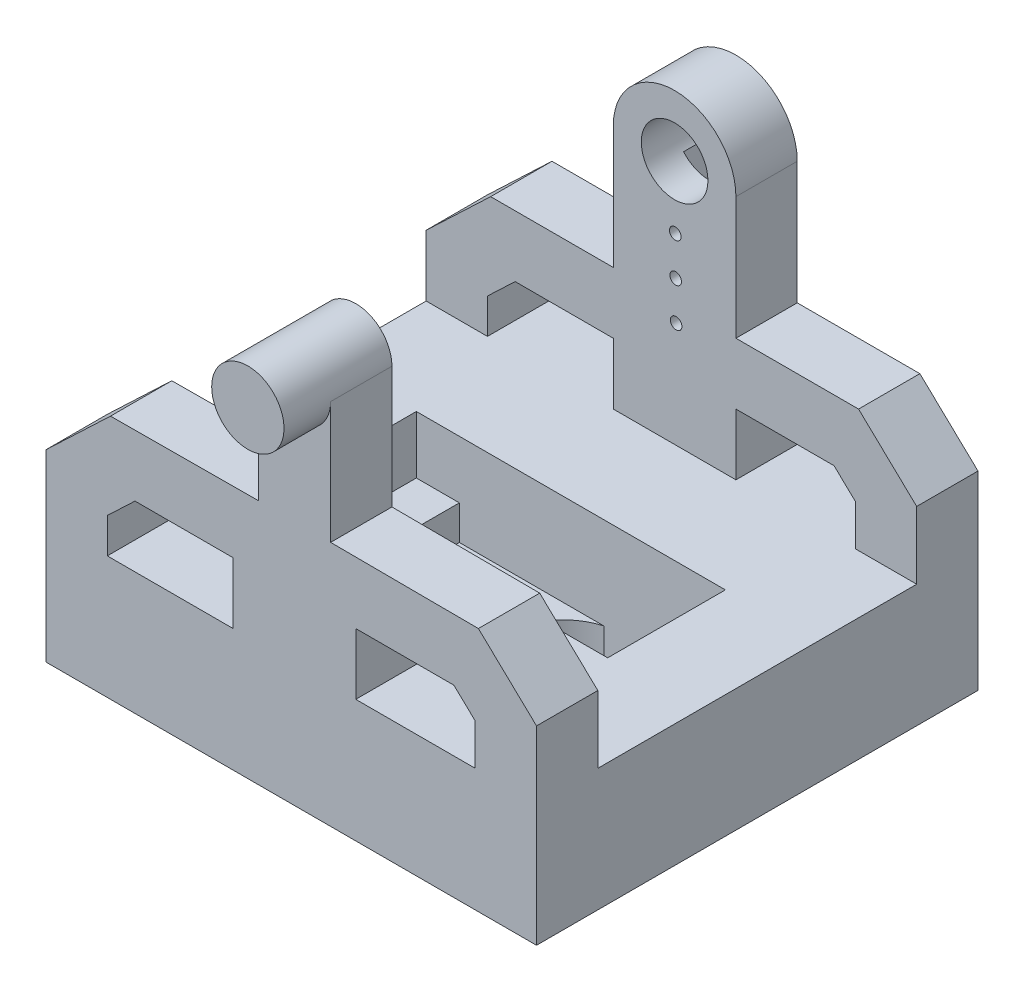
SolidWorks part; units mm, degrees
material "ABS PC"
ref_plane "Front Plane" through (0, 0, 0) normal (0, 0, 1) x (1, 0, 0)
ref_plane "Top Plane" through (0, 0, 0) normal (0, 1, 0) x (1, 0, 0)
ref_plane "Right Plane" through (0, 0, 0) normal (1, 0, 0) x (0, 0, -1)
sketch "Sketch1" plane through (0, 0, 0) normal (0, 1, 0) x (1, 0, 0)
  line L1 (-25.4, -22.86) -> (25.4, -22.86)
  line L2 (-25.4, -22.86) -> (-25.4, 22.86)
  line L3 (-25.4, 22.86) -> (25.4, 22.86)
  line L4 (25.4, -22.86) -> (25.4, 22.86)
  line L5 (-25.4, -22.86) -> (25.4, 22.86) construction
  line L6 (-25.4, 22.86) -> (25.4, -22.86) construction
  line L7 (-16.002, -6.096) -> (16.002, -6.096)
  line L8 (-16.002, -6.096) -> (-16.002, 6.096)
  line L9 (-16.002, 6.096) -> (16.002, 6.096)
  line L10 (16.002, -6.096) -> (16.002, 6.096)
  line L11 (-16.002, -6.096) -> (16.002, 6.096) construction
  line L12 (-16.002, 6.096) -> (16.002, -6.096) construction
  point P0 (0, 0)
  point P6 (0, 0)
  dimension "D1" = 45.72
  dimension "D2" = 50.8
  dimension "D3" = 12.192
  dimension "D4" = 32.004
extrude "Boss-Extrude1" add sketch "Sketch1" along normal blind 12.7
sketch "Sketch2" plane through (0, 0, 0) normal (0, 0, 1) x (1, 0, 0)
  line L0 (-2.2965, 35.8626) -> (-1.5155, 23.9203)
  line L1 (2.4783, 23.9631) -> (3.0032, 35.9195)
  line L14 (-6.0204, 38.1) -> (-6.0204, 25.4)
  line L15 (6.6796, 38.1) -> (6.6796, 25.4)
  line L16 (-6.0204, 25.4) -> (-18.7204, 25.4)
  line L17 (-18.7204, 25.4) -> (-25.4, 19.05)
  line L20 (-25.4, 19.05) -> (-25.4, 12.7)
  line L21 (-25.4, 12.7) -> (25.4, 12.7) construction
  line L22 (-25.4, 12.7) -> (-25.4, 0) construction
  line L23 (-6.0204, 19.05) -> (-16.1837, 19.05)
  line L24 (25.4, 19.6767) -> (25.4, 12.7)
  line L25 (19.3796, 25.4) -> (25.4, 19.6767)
  line L26 (6.6796, 25.4) -> (19.3796, 25.4)
  line L27 (-16.1837, 19.05) -> (-19.05, 16.3252)
  line L28 (-19.05, 16.3252) -> (-19.05, 12.7)
  line L29 (6.6796, 19.05) -> (16.843, 19.05)
  line L30 (16.843, 19.05) -> (19.05, 16.9519)
  line L31 (19.05, 16.9519) -> (19.05, 12.7)
  line L32 (19.05, 12.7) -> (25.4, 12.7)
  line L33 (6.6796, 12.7) -> (-6.0204, 12.7)
  line L34 (-19.05, 12.7) -> (-25.4, 12.7)
  line L35 (-6.0204, 19.05) -> (-6.0204, 12.7)
  line L36 (6.6796, 19.05) -> (6.6796, 12.7)
  arc A0 (6.6796, 38.1) -> (-6.0204, 38.1) centre (0.3296, 38.1) ccw
  circle A2 centre (0.3296, 38.1) radius 1.6719
  arc A3 (-1.5155, 23.9203) -> (2.4783, 23.9631) centre (0.4802, 24.0508) ccw
  arc A4 (3.0032, 35.9195) -> (-2.2965, 35.8626) centre (0.3296, 38.1) ccw
  point P16 (0.3296, 44.45)
  dimension "D3" = 12.7
  dimension "D1" = 25.4
  dimension "D2" = 12.7
  dimension "D4" = 6.35
  dimension "D5" = 6.35
  dimension "D6" = 6.35
extrude "Boss-Extrude2" add sketch "Sketch2" along normal blind 6.35 from surface at -22.86
sketch "Sketch4" plane through (0, 0, 0) normal (0, 0, 1) x (1, 0, 0)
  line L0 (2.4783, 23.9631) -> (3.0032, 35.9195) construction
  line L1 (-2.2965, 35.8626) -> (-1.5155, 23.9203) construction
  line L2 (2.4783, 23.9631) -> (3.0032, 35.9195)
  line L3 (-2.2965, 35.8626) -> (-1.5155, 23.9203)
  arc A0 (-1.5155, 23.9203) -> (2.4783, 23.9631) centre (0.4802, 24.0508) ccw construction
  arc A1 (3.0032, 35.9195) -> (-2.2965, 35.8626) centre (0.3296, 38.1) ccw construction
  arc A2 (-1.5155, 23.9203) -> (2.4783, 23.9631) centre (0.4802, 24.0508) ccw
  arc A3 (3.0032, 35.9195) -> (-2.2965, 35.8626) centre (0.3296, 38.1) ccw
  circle A4 centre (0.3296, 38.1) radius 3.45
  circle A5 centre (0.3988, 31.6504) radius 0.6 construction
  circle A6 centre (0.4417, 27.6506) radius 0.6 construction
  circle A7 centre (0.4845, 23.6508) radius 0.6 construction
  circle A8 centre (0.3988, 31.6504) radius 0.6
  circle A9 centre (0.4417, 27.6506) radius 0.6
  circle A10 centre (0.4845, 23.6508) radius 0.6
extrude "Boss-Extrude3" add sketch "Sketch4" against normal blind 3.556 from surface at -16.51 contours A4 L3 A2 L2
sketch "Sketch5" plane through (0, 0, 0) normal (0, 1, 0) x (1, 0, 0)
  line L6 (5.198, 6.354) -> (16.002, 6.354)
  line L7 (5.198, -6.346) -> (16.002, -6.346)
  line L8 (16.002, -6.346) -> (16.002, 6.354)
  line L9 (5.198, -6.346) -> (-16.002, -6.346)
  line L10 (-16.002, -6.346) -> (-16.002, 6.354)
  line L11 (-16.002, 6.354) -> (5.198, 6.354)
  arc A8 (-0.3022, -3.1694) -> (-0.3022, 3.1774) centre (5.198, 0.004) ccw
  arc A9 (-0.3022, 3.1774) -> (-0.3022, -3.1694) centre (-0.402, 0.004) ccw
  dimension "D1" = 12.7
  dimension "D2" = 3.175
extrude "Boss-Extrude4" add sketch "Sketch5" along normal blind 3.175 contours A8 L7 L8 L6 | A9 A8 L11 L10 L9
sketch "Sketch6" plane through (0, 0, 0) normal (0, 1, 0) x (1, 0, 0)
  line L0 (-11.548, 6.096) -> (-11.548, -6.096)
  line L1 (3.4063, 6.096) -> (-16.002, 6.096) construction
  line L2 (-16.002, -6.096) -> (16.002, -6.096) construction
  line L7 (-11.548, 6.096) -> (-16.002, 6.096)
  line L8 (-16.002, 6.096) -> (-16.002, -6.096)
  line L9 (-16.002, -6.096) -> (-11.548, -6.096)
  line L10 (11.548, -6.096) -> (16.002, -6.096)
  line L11 (16.002, -6.096) -> (16.002, 6.096)
  line L12 (16.002, 6.096) -> (11.548, 6.096)
  line L13 (11.548, 6.096) -> (11.548, -6.096)
  dimension "D1" = 4.454
extrude "Boss-Extrude5" add sketch "Sketch6" along normal blind 3.556 from surface at 3.175 starting at face at (-4.9347, 3.175, -0.0005)
sketch "Sketch7" plane through (0, 0, 0) normal (0, 0, 1) x (1, 0, 0)
  line L0 (0, 12.7) -> (0.3296, 38.1)
  line L1 (-25.4, 12.7) -> (25.4, 12.7) construction
  line L2 (-3.4159, 38.1) -> (-3.4159, 25.475)
  line L3 (10.448, 25.475) -> (-10.352, 25.475) construction
  line L4 (4.0751, 38.1) -> (4.0751, 25.475)
  line L5 (4.0751, 25.475) -> (-3.4159, 25.475)
  line L6 (19.3796, 25.4) -> (4.0751, 25.475)
  line L7 (-3.4159, 25.475) -> (-18.7204, 25.4)
  line L25 (19.05, 16.9519) -> (19.05, 12.7)
  line L26 (19.05, 12.7) -> (25.4, 12.7)
  line L27 (25.4, 12.7) -> (25.4, 19.6767)
  line L28 (25.4, 19.6767) -> (19.3796, 25.4)
  line L29 (19.3796, 25.4) -> (6.6796, 25.4)
  line L30 (6.6796, 25.4) -> (6.6796, 38.1)
  line L31 (-6.0204, 38.1) -> (-6.0204, 25.4)
  line L32 (-6.0204, 25.4) -> (-18.7204, 25.4)
  line L33 (-18.7204, 25.4) -> (-25.4, 19.05)
  line L34 (-25.4, 19.05) -> (-25.4, 12.7)
  line L35 (-25.4, 12.7) -> (-19.05, 12.7)
  line L36 (-19.05, 12.7) -> (-19.05, 16.3252)
  line L37 (-19.05, 16.3252) -> (-16.1837, 19.05)
  line L38 (-16.1837, 19.05) -> (-6.0204, 19.05)
  line L39 (-6.0204, 19.05) -> (-6.0204, 12.7)
  line L40 (-6.0204, 12.7) -> (6.6796, 12.7)
  line L41 (6.6796, 12.7) -> (6.6796, 19.05)
  line L42 (6.6796, 19.05) -> (16.843, 19.05)
  line L43 (16.843, 19.05) -> (19.05, 16.9519)
  line L44 (19.05, 16.9519) -> (19.05, 12.7)
  line L45 (19.05, 12.7) -> (25.4, 12.7)
  line L46 (25.4, 12.7) -> (25.4, 19.6767)
  line L47 (25.4, 19.6767) -> (19.3796, 25.4)
  line L52 (-18.7204, 25.4) -> (-25.4, 19.05)
  line L53 (-25.4, 19.05) -> (-25.4, 12.7)
  line L54 (-25.4, 12.7) -> (-19.05, 12.7)
  line L55 (-19.05, 12.7) -> (-19.05, 16.3252)
  line L56 (-19.05, 16.3252) -> (-16.1837, 19.05)
  line L57 (-16.1837, 19.05) -> (-6.0204, 19.05)
  line L58 (-6.0204, 19.05) -> (-6.0204, 12.7)
  line L59 (-6.0204, 12.7) -> (6.6796, 12.7)
  line L60 (6.6796, 12.7) -> (6.6796, 19.05)
  line L61 (6.6796, 19.05) -> (16.843, 19.05)
  line L62 (16.843, 19.05) -> (19.05, 16.9519)
  circle A0 centre (0.3296, 38.1) radius 3.7455
  arc A2 (6.6796, 38.1) -> (-6.0204, 38.1) centre (0.3296, 38.1) ccw
  dimension "D1" = 0
extrude "Boss-Extrude6" add sketch "Sketch7" against normal blind 6.35 from surface at 22.86 separate body
sketch "Sketch8" plane through (0, 0, 0) normal (0, 0, 1) x (1, 0, 0)
  circle A0 centre (0.3296, 38.1) radius 3.7455
extrude "Boss-Extrude7" add sketch "Sketch8" along normal blind 4.826 from surface
